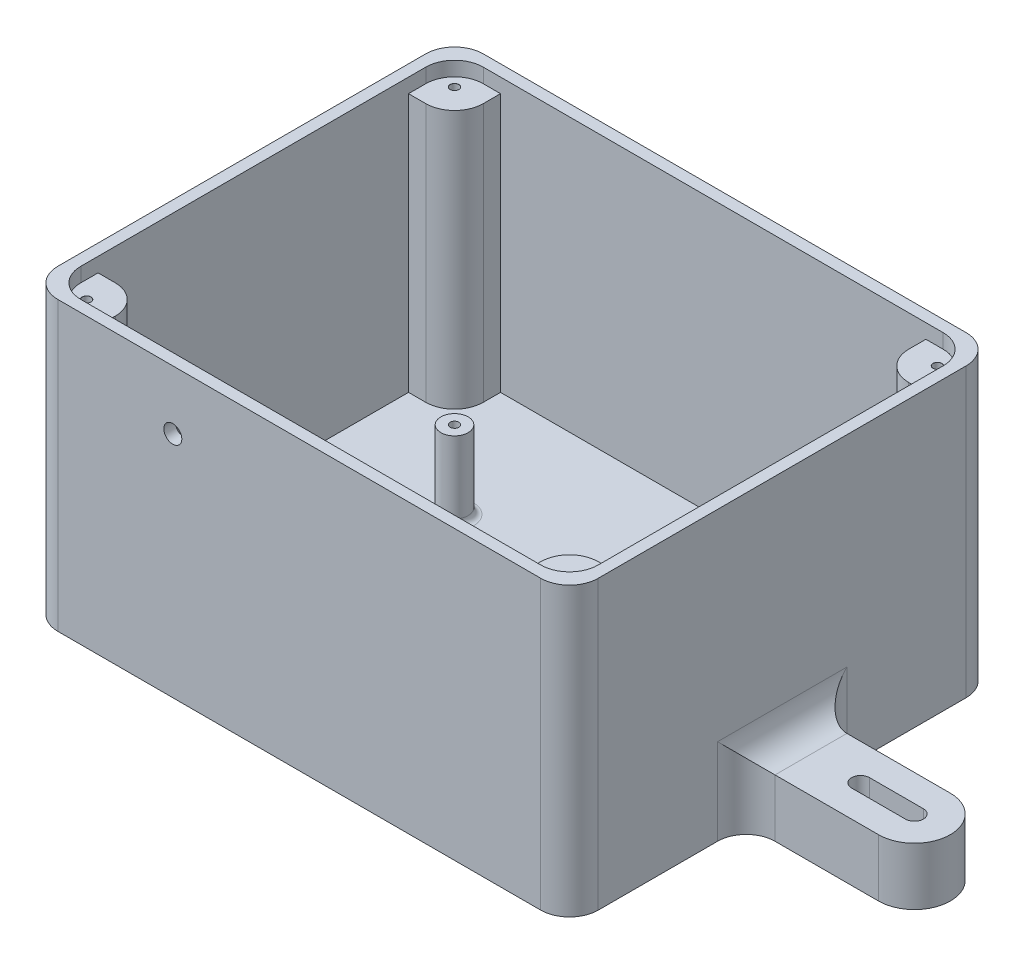
SolidWorks part; units mm, degrees
ref_plane "Plano frontal" through (0, 0, 0) normal (0, 0, 1) x (1, 0, 0)
ref_plane "Plano superior" through (0, 0, 0) normal (0, 1, 0) x (1, 0, 0)
ref_plane "Plano direito" through (0, 0, 0) normal (1, 0, 0) x (0, 0, -1)
ref_plane "Plano1" through (0, 0, -4.75) normal (0, 0, 1) x (1, 0, 0)
sketch "Esboço1" plane through (0, 0, -4.75) normal (0, 0, 1) x (1, 0, 0)
  line L0 (100, 27) -> (95.25, 27)
  line L1 (95.25, 27) -> (95.25, 26)
  line L2 (95.25, 26) -> (100, 26)
  line L3 (100, 26) -> (100, 27)
  line L4 (95.25, 27) -> (95.25, 26) construction
revolve "Revolução1" add sketch "Esboço1" angle 180 about L4
sketch "Esboço2" plane through (0, 0, -4.75) normal (0, 0, 1) x (1, 0, 0)
  line L0 (90.5, 100) -> (100, 100)
  line L1 (100, 100) -> (100, 26)
  line L2 (100, 26) -> (90.5, 26)
  line L3 (90.5, 26) -> (90.5, 100)
extrude "Ressalto-extrusão1" add sketch "Esboço2" along normal blind 8.75
sketch "Esboço3" plane through (90.5, 0, 0) normal (-1, 0, 0) x (0, 0, 1)
  line L0 (-4.75, 27) -> (4, 27)
  line L1 (4, 27) -> (4, 100)
  line L2 (4, 100) -> (-4.75, 100)
  line L3 (-4.75, 100) -> (-4.75, 27)
extrude "Corte-extrusão1" cut sketch "Esboço3" against normal blind 1.5
sketch "Esboço4" plane through (0, 0, -4.75) normal (0, 0, -1) x (-1, 0, 0)
  line L0 (-92, 27) -> (-92, 100)
  line L1 (-92, 100) -> (-100, 100)
  line L2 (-100, 100) -> (-100, 27)
  line L3 (-100, 27) -> (-92, 27)
extrude "Corte-extrusão2" cut sketch "Esboço4" against normal blind 4.75
sketch "Esboço5" plane through (92, 0, 0) normal (-1, 0, 0) x (0, 0, 1)
  line L0 (4, 32) -> (0, 32)
  line L1 (0, 32) -> (0, 100)
  line L2 (0, 100) -> (4, 100)
  line L3 (4, 100) -> (4, 32)
extrude "Ressalto-extrusão2" add sketch "Esboço5" along normal blind 52
sketch "Esboço6" plane through (40, 0, 0) normal (-1, 0, 0) x (0, 0, 1)
  line L0 (4, 26) -> (0, 26)
  line L1 (0, 26) -> (0, 100)
  line L2 (0, 100) -> (4, 100)
  line L3 (4, 100) -> (4, 26)
extrude "Ressalto-extrusão3" add sketch "Esboço6" along normal blind 80
sketch "Esboço7" plane through (100, 0, 0) normal (1, 0, 0) x (0, 0, -1)
  line L0 (0, 100) -> (0, 26)
  line L1 (0, 26) -> (-4, 26)
  line L2 (-4, 26) -> (-4, 100)
  line L3 (-4, 100) -> (0, 100)
extrude "Ressalto-extrusão4" add sketch "Esboço7" along normal blind 40
sketch "Esboço8" plane through (140, 0, 0) normal (1, 0, 0) x (0, 0, -1)
  line L0 (140, 26) -> (-4, 26)
  line L1 (-4, 26) -> (-4, 100)
  line L2 (-4, 100) -> (140, 100)
  line L3 (140, 100) -> (140, 26)
extrude "Ressalto-extrusão5" add sketch "Esboço8" along normal blind 4
sketch "Esboço9" plane through (-40, 0, 0) normal (-1, 0, 0) x (0, 0, 1)
  line L0 (-140, 26) -> (-140, 100)
  line L1 (-140, 100) -> (4, 100)
  line L2 (4, 100) -> (4, 26)
  line L3 (4, 26) -> (-140, 26)
extrude "Ressalto-extrusão6" add sketch "Esboço9" along normal blind 4
sketch "Esboço10" plane through (0, 0, -140) normal (0, 0, -1) x (-1, 0, 0)
  line L0 (-144, 26) -> (-144, 100)
  line L1 (-144, 100) -> (44, 100)
  line L2 (44, 100) -> (44, 26)
  line L3 (44, 26) -> (-144, 26)
extrude "Ressalto-extrusão7" add sketch "Esboço10" along normal blind 4
sketch "Esboço11" plane through (0, 26, 0) normal (0, -1, 0) x (1, 0, 0)
  line L0 (144, -144) -> (-44, -144)
  line L1 (-44, -144) -> (-44, 4)
  line L2 (-44, 4) -> (144, 4)
  line L3 (144, 4) -> (144, -144)
extrude "Ressalto-extrusão8" add sketch "Esboço11" along normal blind 26
sketch "Esboço12" plane through (0, 26, 0) normal (0, 1, 0) x (-1, 0, 0)
  line L0 (-140, -140) -> (40, -140)
  line L1 (40, -140) -> (40, 0)
  line L2 (40, 0) -> (-90.5, 0)
  line L3 (-90.5, 0) -> (-90.5, -4.75)
  line L4 (-100, -4.75) -> (-100, 0)
  line L5 (-100, 0) -> (-140, 0)
  line L6 (-140, 0) -> (-140, -140)
  arc A0 (-90.5, -4.75) -> (-100, -4.75) centre (-95.25, -4.75) cw
extrude "Corte-extrusão3" cut sketch "Esboço12" against normal blind 21
ref_plane "Plano2" through (0, 0, 0) normal (0, -1, 0) x (1, 0, 0)
sketch "Esboço13" plane through (0, 0, 0) normal (0, -1, 0) x (1, 0, 0)
  line L0 (144, -82.5) -> (190, -82.5)
  line L1 (190, -57.5) -> (144, -57.5)
  line L2 (144, -57.5) -> (144, -82.5)
  arc A0 (190, -82.5) -> (190, -57.5) centre (190, -70) ccw
extrude "Ressalto-extrusão9" add sketch "Esboço13" against normal blind 20
sketch "Esboço14" plane through (0, 0, 0) normal (0, -1, 0) x (1, 0, 0)
  line L0 (190, -66.875) -> (171.25, -66.875)
  line L1 (171.25, -73.125) -> (190, -73.125)
  arc A0 (190, -73.125) -> (190, -66.875) centre (190, -70) ccw
  arc A1 (171.25, -66.875) -> (171.25, -73.125) centre (171.25, -70) ccw
extrude "Corte-extrusão4" cut sketch "Esboço14" against normal through all
sketch "Esboço15" plane through (0, 0, 0) normal (0, -1, 0) x (1, 0, 0)
  line L0 (-44, -57.5) -> (-90, -57.5)
  line L1 (-90, -82.5) -> (-44, -82.5)
  line L2 (-44, -82.5) -> (-44, -57.5)
  arc A0 (-90, -57.5) -> (-90, -82.5) centre (-90, -70) ccw
extrude "Ressalto-extrusão10" add sketch "Esboço15" against normal blind 20
sketch "Esboço16" plane through (0, 20, 0) normal (0, 1, 0) x (-1, 0, 0)
  line L0 (71.25, -73.125) -> (90, -73.125)
  line L1 (90, -66.875) -> (71.25, -66.875)
  arc A0 (71.25, -66.875) -> (71.25, -73.125) centre (71.25, -70) ccw
  arc A1 (90, -73.125) -> (90, -66.875) centre (90, -70) ccw
extrude "Corte-extrusão5" cut sketch "Esboço16" against normal through all
sketch "Esboço17" plane through (0, 5, 0) normal (0, 1, 0) x (-1, 0, 0)
  line L0 (24, -124) -> (40, -124)
  line L1 (40, -124) -> (40, -140)
  line L2 (40, -140) -> (24, -140)
  line L3 (24, -140) -> (24, -124)
extrude "Ressalto-extrusão11" add sketch "Esboço17" along normal blind 90
sketch "Esboço18" plane through (0, 5, 0) normal (0, 1, 0) x (-1, 0, 0)
  line L0 (-124, -140) -> (-140, -140)
  line L1 (-140, -140) -> (-140, -124)
  line L2 (-140, -124) -> (-124, -124)
  line L3 (-124, -124) -> (-124, -140)
extrude "Ressalto-extrusão12" add sketch "Esboço18" along normal blind 90
sketch "Esboço19" plane through (0, 5, 0) normal (0, 1, 0) x (-1, 0, 0)
  line L0 (-124, -16) -> (-140, -16)
  line L1 (-140, -16) -> (-140, 0)
  line L2 (-140, 0) -> (-124, 0)
  line L3 (-124, 0) -> (-124, -16)
extrude "Ressalto-extrusão13" add sketch "Esboço19" along normal blind 90
sketch "Esboço20" plane through (0, 5, 0) normal (0, 1, 0) x (-1, 0, 0)
  line L0 (24, -16) -> (24, 0)
  line L1 (24, 0) -> (40, 0)
  line L2 (40, 0) -> (40, -16)
  line L3 (40, -16) -> (24, -16)
extrude "Ressalto-extrusão14" add sketch "Esboço20" along normal blind 90
sketch "Esboço21" plane through (0, 5, 0) normal (0, 1, 0) x (-1, 0, 0)
  line L0 (-9.5, -4.75) -> (-9.5, 0)
  line L1 (-9.5, 0) -> (0, 0)
  line L2 (0, 0) -> (0, -4.75)
  arc A0 (0, -4.75) -> (-9.5, -4.75) centre (-4.75, -4.75) cw
extrude "Ressalto-extrusão15" add sketch "Esboço21" along normal blind 22
ref_plane "Plano3" through (0, 0, -95.25) normal (0, 0, 1) x (1, 0, 0)
sketch "Esboço22" plane through (0, 0, -95.25) normal (0, 0, 1) x (1, 0, 0)
  line L0 (9.5, 27) -> (4.75, 27)
  line L1 (4.75, 27) -> (4.75, 5)
  line L2 (4.75, 5) -> (9.5, 5)
  line L3 (9.5, 5) -> (9.5, 27)
  line L4 (4.75, 27) -> (4.75, 5) construction
revolve "Revolução2" add sketch "Esboço22" angle 360 about L4
hole_wizard "Furo de diâmetro Ø3.0 (3)1" positions "Esboço24" profile "Esboço23" hole size "Ø3.0" standard "Ansi Metric"
sketch "Esboço24" plane through (0, 95, 0) normal (0, 1, 0) x (1, 0, 0)
  point P0 (-34, 6)
  point P1 (134, 6)
  point P2 (134, 134)
  point P3 (-34, 134)
sketch "Esboço23" plane through (-34, 95, -6) normal (1, 0, 0) x (0, 0, 1)
  line L0 (0, 0) -> (0, 15.9013)
  line L1 (0, 15.9013) -> (1.5, 15)
  line L2 (1.5, 15) -> (1.5, 0)
  line L5 (1.5, 0) -> (0, 0)
  line L10 (0, 15.9013) -> (-1.5, 15) construction
  line L11 (0, -6.35) -> (0, 107.95) construction
  dimension "Hole Dia." = 3
  dimension "Hole Depth" = 15
  dimension "Drill Angle" = 118
hole_wizard "Furo de diâmetro Ø3.0 (3)2" positions "Esboço26" profile "Esboço25" hole size "Ø3.0" standard "Ansi Metric"
sketch "Esboço26" plane through (0, 27, 0) normal (0, 1, 0) x (1, 0, 0)
  point P0 (95.25, 4.75)
  point P1 (4.75, 4.75)
  point P2 (4.75, 95.25)
sketch "Esboço25" plane through (95.25, 27, -4.75) normal (1, 0, 0) x (0, 0, 1)
  line L0 (0, 0) -> (0, 15.9013)
  line L1 (0, 15.9013) -> (1.5, 15)
  line L2 (1.5, 15) -> (1.5, 0)
  line L5 (1.5, 0) -> (0, 0)
  line L10 (0, 15.9013) -> (-1.5, 15) construction
  line L11 (0, -6.35) -> (0, 107.95) construction
  dimension "Hole Dia." = 3
  dimension "Hole Depth" = 15
  dimension "Drill Angle" = 118
hole_wizard "Broca de rosquear para helicoide M61" positions "Esboço28" profile "Esboço27" hole size "M6x1.0" standard "Ansi Metric"
sketch "Esboço28" plane through (0, 0, 4) normal (0, 0, 1) x (1, 0, 0)
  point P0 (6, 79.5)
sketch "Esboço27" plane through (6, 79.5, 4) normal (1, 0, 0) x (0, -1, 0)
  line L0 (0, 0) -> (0, 4)
  line L1 (0, 4) -> (3.125, 4)
  line L2 (3.125, 4) -> (3.125, 0)
  line L5 (3.125, 0) -> (0, 0)
  line L11 (0, -6.35) -> (0, 107.95) construction
  dimension "Thru Hole Dia." = 6.25
  dimension "Thru Hole Depth" = 4
chamfer "Chanfro1" distance 0.025 angle 45 7 edges at (-34, 95, -132.5) (134, 95, -132.5) (134, 95, -4.5) (-34, 95, -4.5) (4.75, 27, -93.75) (4.75, 27, -3.25) (95.25, 27, -3.25)
fillet "Filete1" radius 2 3 edges at (92, 32, 2) (40, 26, 2) (40, 32, 2)
fillet "Filete2" radius 10 18 edges at (124, 50, -124) (-44, 10, -82.5) (-44, 20, -70) (-44, 10, -57.5) (144, 10, -82.5) (144, 10, -57.5) (144, 20, -70) (140, 97.5, -140) (140, 97.5, 0) (-24, 50, -16) (-40, 97.5, 0) (-40, 97.5, -140) (144, 50, -144) (-24, 50, -124) (-44, 50, -144) (124, 50, -16) (-44, 50, 4) (144, 50, 4)
sketch "Esboço35" plane through (0, 0, -95.25) normal (0, 0, 1) x (1, 0, 0)
  line L0 (100, 27) -> (95.25, 27)
  line L1 (95.25, 27) -> (95.25, 5)
  line L2 (95.25, 5) -> (100, 5)
  line L3 (100, 5) -> (100, 27)
  line L4 (95.25, 27) -> (95.25, 5) construction
revolve "Revolução3" add sketch "Esboço35" angle 360 about L1
sketch "Esboço42" plane through (0, 0, -95.25) normal (0, 0, 1) x (1, 0, 0)
  line L0 (96.775, 27) -> (95.25, 27)
  line L1 (95.25, 27) -> (95.25, 11.0987)
  line L2 (95.25, 11.0987) -> (96.75, 12)
  line L3 (96.75, 12) -> (96.75, 26.975)
  line L4 (96.75, 26.975) -> (96.775, 27)
  line L5 (95.25, 27) -> (95.25, 11.0987) construction
revolve "Corte-Revolução1" cut sketch "Esboço42" angle 360 about L1
fillet "Filete3" radius 2 8 edges at (0, 5, -2.375) (9.5, 5, -2.375) (4.75, 5, -9.5) (100, 5, -2.375) (95.25, 5, -9.5) (90.5, 5, -2.375) (95.25, 5, -100) (4.75, 5, -100)
sketch "Esboço43" plane through (0, 0, 4) normal (0, 0, 1) x (1, 0, 0)
  line L0 (42, 32) -> (40, 32) construction
  line L1 (90, 32) -> (92, 32) construction
  line L2 (42, 26) -> (40, 26) construction
  line L4 (40, 26) -> (92, 26)
  line L5 (40, 26) -> (40, 32)
  line L6 (40, 32) -> (92, 32)
  line L7 (92, 26) -> (92, 32)
extrude "Ressalto-extrusão16" add sketch "Esboço43" against normal blind 4
sketch "Esboço44" plane through (0, 27, 0) normal (0, 1, 0) x (-1, 0, 0)
  line L0 (-9.5, -4.75) -> (-9.5, 0)
  line L1 (-9.5, 0) -> (0, 0)
  line L2 (0, 0) -> (0, -4.75)
  line L3 (-100, 0) -> (-100, -4.75)
  line L4 (-90.5, 0) -> (-100, 0)
  line L5 (-90.5, -4.75) -> (-90.5, 0)
  circle A0 centre (-4.75, -95.25) radius 4.75
  circle A1 centre (-95.25, -95.25) radius 4.75
  arc A2 (-9.5, -4.75) -> (0, -4.75) centre (-4.75, -4.75) ccw
  circle A3 centre (-4.75, -95.25) radius 1.525
  circle A4 centre (-95.25, -95.25) radius 1.525
  circle A5 centre (-4.75, -4.75) radius 1.525
  circle A6 centre (-95.25, -4.75) radius 1.525
  arc A7 (-90.5, -4.75) -> (-100, -4.75) centre (-95.25, -4.75) cw
extrude "Ressalto-extrusão17" add sketch "Esboço44" along normal mid plane 10
